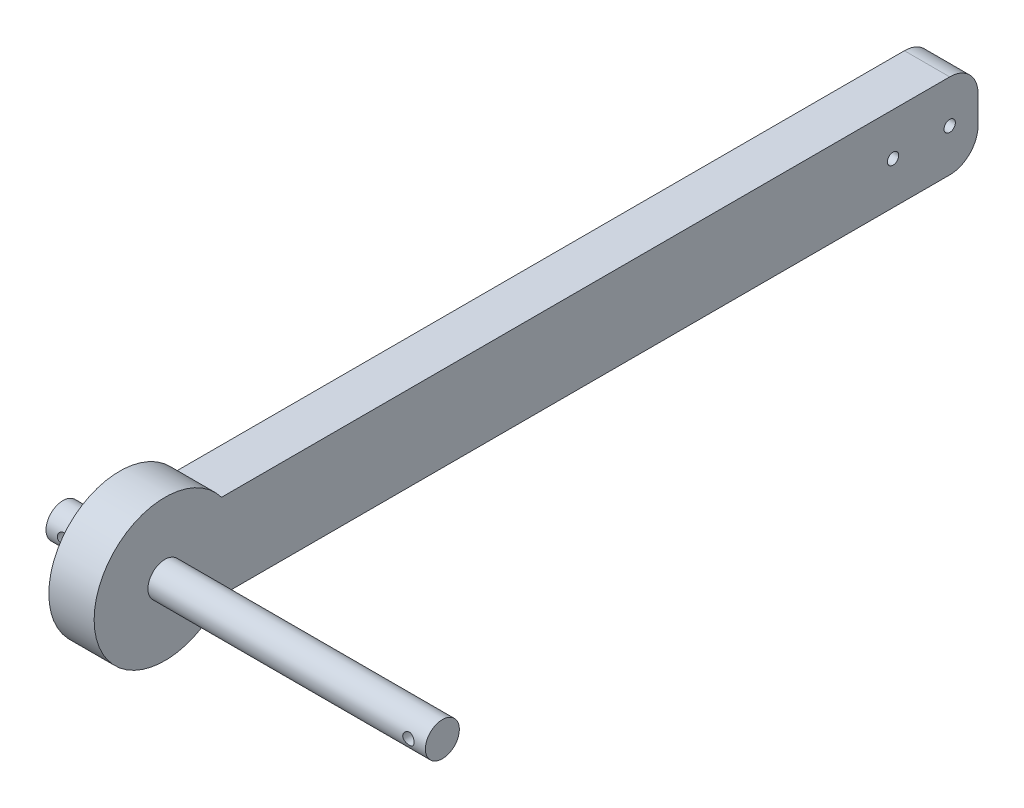
SolidWorks part; units mm, degrees
ref_plane "前视基准面" through (0, 0, 0) normal (0, 0, 1) x (1, 0, 0)
ref_plane "上视基准面" through (0, 0, 0) normal (0, 1, 0) x (1, 0, 0)
ref_plane "右视基准面" through (0, 0, 0) normal (1, 0, 0) x (0, 0, -1)
other "Configuration Table"
sketch "草图1" plane through (0, 0, 0) normal (1, 0, 0) x (0, 0, -1)
  line L1 (0, 0) -> (150, 0)
  line L2 (0, 0) -> (0, 15)
  line L3 (0, 15) -> (150, 15)
  line L4 (150, 0) -> (150, 15)
  dimension "D1" = 15
  dimension "D2" = 150
extrude "凸台-拉伸1" add sketch "草图1" along normal blind 8
fillet "圆角1" radius 5 4 edges at (4, 0, -150) (4, 15, -150) (4, 0, 0) (4, 15, 0)
sketch "草图6" plane through (8, 0, 0) normal (1, 0, 0) x (0, 0, -1)
  circle A0 centre (6.4, 7.5) radius 12.5
extrude "凸台-拉伸2" add sketch "草图6" against normal up to surface (8 mm away) up to face at (0, 7.5, -75)
sketch "草图11" plane through (0, 0, 0) normal (-1, 0, 0) x (0, 0, 1)
  line L0 (-150, 7.5) -> (-91.0607, 7.5) construction
  line L1 (-150, 5) -> (-150, 10) construction
  line L2 (100, 7.5) -> (83.7402, 7.5) construction
  line L3 (100, 10) -> (100, 5) construction
  circle A0 centre (-145, 7.5) radius 1
  circle A1 centre (-135, 7.5) radius 1
  circle A2 centre (85, 7.5) radius 1
  circle A3 centre (95, 7.5) radius 1
  dimension "D2" = 2
  dimension "D3" = 2
  dimension "D7" = 2
  dimension "D8" = 2
  dimension "D1" = 10
  dimension "D4" = 5
  dimension "D5" = 10
  dimension "D6" = 5
extrude "切除-拉伸8" cut sketch "草图11" against normal blind 10
sketch "草图15" plane through (0, 0, 0) normal (-1, 0, 0) x (0, 0, 1)
  circle A2 centre (-6.4, 7.5) radius 3
  dimension "D1" = 6
extrude "凸台-拉伸5" add sketch "草图15" along normal blind 10 and the other way blind 57
sketch "草图16" plane through (0, 0, 0) normal (0, 0, 1) x (1, 0, 0)
  line L0 (-10, 7.5) -> (-24.7951, 7.5) construction
  line L1 (-10, 10.5) -> (-10, 4.5) construction
  line L2 (57, 7.5) -> (28.4852, 7.5) construction
  line L3 (57, 4.5) -> (57, 10.5) construction
  circle A0 centre (-7, 7.5) radius 1
  circle A1 centre (54, 7.5) radius 1
  dimension "D2" = 2
  dimension "D3" = 2
  dimension "D1" = 3
  dimension "D4" = 3
extrude "切除-拉伸9" cut sketch "草图16" against normal up to next
